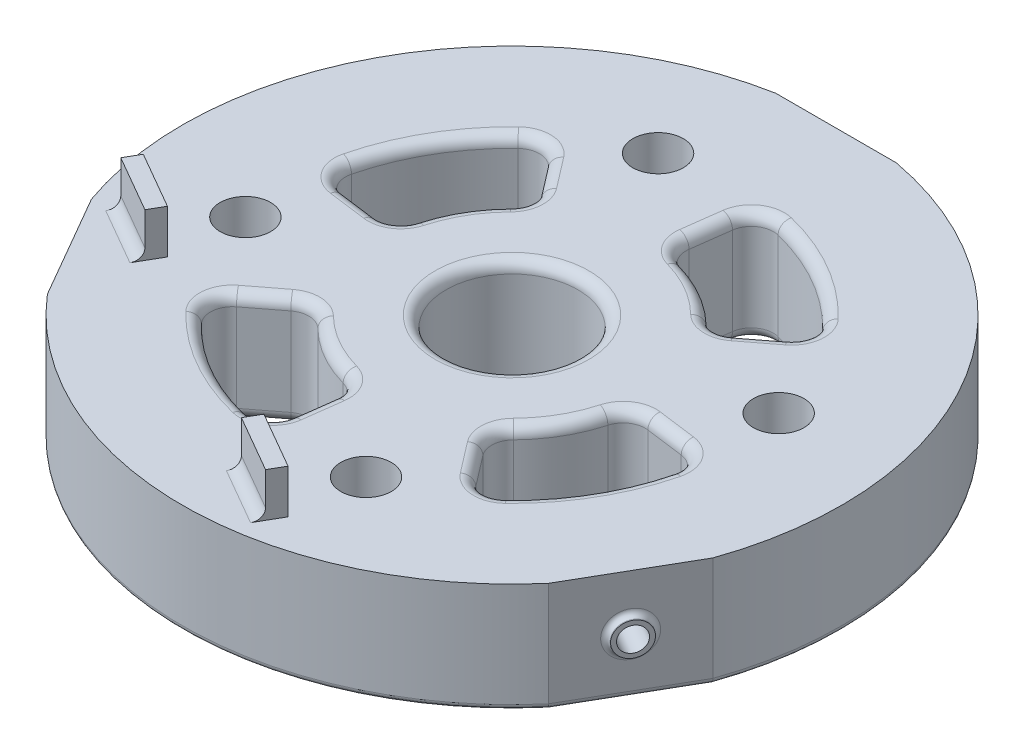
SolidWorks part; units mm, degrees
ref_plane "前视基准面" through (0, 0, 0) normal (0, 0, 1) x (1, 0, 0)
ref_plane "上视基准面" through (0, 0, 0) normal (0, 1, 0) x (1, 0, 0)
ref_plane "右视基准面" through (0, 0, 0) normal (1, 0, 0) x (0, 0, -1)
other "Configuration Table"
sketch "草图1" plane through (0, 0, 0) normal (0, 1, 0) x (1, 0, 0)
  line L0 (0, 0) -> (0, 30) construction
  line L1 (0, 0) -> (-25.9808, -15) construction
  line L2 (0, 0) -> (25.9808, -15) construction
  line L3 (-5.4819, 29.4949) -> (5.4819, 29.4949)
  line L4 (-5, 24.4949) -> (5, 24.4949)
  line L5 (28.2843, -10) -> (22.8024, -19.4949)
  line L6 (23.7132, -7.9173) -> (18.7132, -16.5776)
  line L7 (-22.8024, -19.4949) -> (-28.2843, -10)
  line L8 (-18.7132, -16.5776) -> (-23.7132, -7.9173)
  arc A0 (-5.4819, 29.4949) -> (-28.2843, -10) centre (0, 0) ccw
  arc A1 (-5, 24.4949) -> (-23.7132, -7.9173) centre (0, 0) ccw
  arc A2 (23.7132, -7.9173) -> (5, 24.4949) centre (0, 0) ccw
  arc A3 (28.2843, -10) -> (5.4819, 29.4949) centre (0, 0) ccw
  arc A4 (-18.7132, -16.5776) -> (18.7132, -16.5776) centre (0, 0) ccw
  arc A5 (-22.8024, -19.4949) -> (22.8024, -19.4949) centre (0, 0) ccw
  point P21 (0, 0)
  dimension "D1" = 60
  dimension "D2" = 50
  dimension "D3" = 120
  dimension "D4" = 120
  dimension "D5" = 5
  dimension "D6" = 10
  dimension "D7" = 3
extrude "凸台-拉伸1" add sketch "草图1" along normal blind 10
sketch "草图2" plane through (25.5433, 0, 14.7474) normal (0.866, 0, 0.5) x (0.5, 0, -0.866)
  circle A0 centre (0, 5) radius 1.1
  dimension "D1" = 2.2
  dimension "D2" = 5
extrude "切除-拉伸1" cut sketch "草图2" against normal blind 10
sketch "草图3" plane through (21.2132, 0, 12.2474) normal (-0.866, 0, -0.5) x (-0.5, 0, 0.866)
  line L0 (0, 10) -> (0, 0) construction
  circle A0 centre (0, 5) radius 3.1
  dimension "D1" = 6.2
  dimension "D2" = 5
extrude "切除-拉伸2" [suppressed] cut sketch "草图3" against normal blind 0.6
pattern_circular "阵列(圆周)1" count 3 over 360 about axis through (0, 10, 0) along (0, -1, 0) of "切除-拉伸1"
sketch "草图4" plane through (25.5433, 0, 14.7474) normal (0.866, 0, 0.5) x (0.5, 0, -0.866)
  circle A0 centre (0, 5) radius 1.1
  circle A1 centre (0, 5) radius 1.5
  dimension "D1" = 2.2
  dimension "D2" = 3
extrude "凸台-拉伸2" add sketch "草图4" along normal blind 0.6
fillet "圆角1" radius 0.5 1 edges at (24.7933, 5, 16.0465)
pattern_circular "阵列(圆周)2" count 3 over 360 about axis through (0, 0, 0) along (0, 1, 0) of "凸台-拉伸2"
fillet "圆角2" radius 0.5 2 edges at (1.5, 5, -29.4949) (-26.2933, 5, 13.4484)
sketch "草图5" plane through (0, 10, 0) normal (0, 1, 0) x (1, 0, 0)
  circle A0 centre (0, 0) radius 25
extrude "凸台-拉伸3" add sketch "草图5" against normal blind 10
sketch "草图6" plane through (0, 10, 0) normal (0, 1, 0) x (1, 0, 0)
  line L0 (10.1645, 17.6055) -> (0, 0) construction
  line L5 (0, 0) -> (16.3306, -9.4285) construction
  line L6 (-6.1154, 19.4078) -> (19.8654, 4.4078) construction
  line L7 (19.8654, 4.4078) -> (6.1154, -19.4078) construction
  line L8 (-6.1154, 19.4078) -> (-19.8654, -4.4078) construction
  line L9 (-19.8654, -4.4078) -> (6.1154, -19.4078) construction
  line L10 (0, 0) -> (25.5433, -14.7474) construction
  line L11 (24.5433, -16.4795) -> (26.5433, -13.0154) construction
  circle A0 centre (-6.1154, 19.4078) radius 2.3
  circle A1 centre (19.8654, 4.4078) radius 2.3
  circle A2 centre (6.1154, -19.4078) radius 2.3
  circle A3 centre (-19.8654, -4.4078) radius 2.3
  point P10 (-6.875, -11.9078)
  point P12 (6.875, 11.9078)
  point P13 (-12.9904, 7.5)
  point P14 (12.9904, -7.5)
  dimension "D3" = 4.6
  dimension "D1" = 30
  dimension "D2" = 27.5
extrude "切除-拉伸3" cut sketch "草图6" against normal blind 10
sketch "草图7" plane through (0, 0, 0) normal (0, -1, 0) x (1, 0, 0)
  circle A0 centre (-19.8654, 4.4078) radius 3.65
  circle A1 centre (6.1154, 19.4078) radius 3.65
  circle A2 centre (19.8654, -4.4078) radius 3.65
  circle A3 centre (-6.1154, -19.4078) radius 3.65
  dimension "D1" = 7.3
  dimension "D2" = 7.3
  dimension "D3" = 7.3
  dimension "D4" = 7.3
extrude "切除-拉伸4" cut sketch "草图7" against normal blind 4
sketch "草图8" plane through (0, 10, 0) normal (0, 1, 0) x (1, 0, 0)
  line L0 (-19.8654, -4.4078) -> (6.1154, -19.4078) construction
  line L1 (-22.8654, -9.604) -> (3.1154, -24.604) construction
  line L2 (-19.8654, -4.4078) -> (-22.8654, -9.604) construction
  line L3 (-20.2673, -11.104) -> (-25.4635, -8.104)
  line L4 (-25.4635, -8.104) -> (-26.2135, -9.403)
  line L5 (-26.2135, -9.403) -> (-21.0173, -12.403)
  line L6 (-20.2673, -11.104) -> (-21.0173, -12.403)
  line L7 (0, 0) -> (-6.875, -11.9078) construction
  line L8 (-25.4635, -8.104) -> (-26.2135, -9.403)
  line L9 (-20.2673, -11.104) -> (-21.0173, -12.403)
  line L10 (-25.4635, -8.104) -> (-26.2135, -9.403)
  line L11 (-20.2673, -11.104) -> (-21.0173, -12.403)
  line L12 (-25.4635, -8.104) -> (-26.2135, -9.403)
  line L13 (-20.2673, -11.104) -> (-21.0173, -12.403)
  line L14 (6.1154, -19.4078) -> (3.1154, -24.604) construction
  line L15 (0.5173, -23.104) -> (-0.2327, -24.403)
  line L16 (5.7135, -26.104) -> (4.9635, -27.403)
  line L17 (0.5173, -23.104) -> (-0.2327, -24.403)
  line L18 (5.7135, -26.104) -> (4.9635, -27.403)
  line L19 (0.5173, -23.104) -> (-0.2327, -24.403)
  line L20 (5.7135, -26.104) -> (4.9635, -27.403)
  line L21 (0.5173, -23.104) -> (-0.2327, -24.403)
  line L22 (4.9635, -27.403) -> (-0.2327, -24.403)
  line L23 (5.7135, -26.104) -> (4.9635, -27.403)
  line L24 (0.5173, -23.104) -> (5.7135, -26.104)
  point P13 (-23.6154, -10.903)
  point P23 (2.3654, -25.903)
  dimension "D2" = 1.5
  dimension "D3" = 6
  dimension "D1" = 6
extrude "凸台-拉伸4" add sketch "草图8" along normal blind 4 contours L6 L3 L4 L5 | L24 L15 L22 L16
fillet "圆角3" radius 1 2 edges at (2.3654, 10, 25.903) (-23.6154, 10, 10.903)
fillet "圆角4" radius 0.5 10 edges at (-25.5433, 0, 14.7474) (0, 0, 30) (25.5433, 0, 14.7474) (25.9808, 0, -15) (0, 0, -29.4949) (-25.9808, 0, -15) (-6.1154, 0, -23.0578) (19.8654, 0, -8.0578) (6.1154, 0, 15.7578) (-19.8654, 0, 0.7578)
sketch "草图9" plane through (0, 0, 0) normal (0, -1, 0) x (1, 0, 0)
  line L0 (6.1154, 19.4078) -> (19.8654, -4.4078) construction
  line L1 (0, 0) -> (12.9904, 7.5) construction
  line L4 (0, 0) -> (-10, 17.3205) construction
  line L11 (12.3931, 1.6316) -> (19.8289, 2.6105)
  line L12 (7.6095, 9.9169) -> (12.1752, 15.8671)
  line L13 (-1.6316, 12.3931) -> (-2.6105, 19.8289)
  line L14 (-9.9169, 7.6095) -> (-15.8671, 12.1752)
  line L15 (-12.3931, -1.6316) -> (-19.8289, -2.6105)
  line L16 (-7.6095, -9.9169) -> (-12.1752, -15.8671)
  line L17 (9.9169, -7.6095) -> (15.8671, -12.1752)
  line L18 (1.6316, -12.3931) -> (2.6105, -19.8289)
  circle A0 centre (0, 0) radius 6
  arc A1 (19.8289, 2.6105) -> (12.1752, 15.8671) centre (0, 0) ccw
  arc A2 (1.6316, -12.3931) -> (9.9169, -7.6095) centre (0, 0) ccw
  arc A3 (-2.6105, 19.8289) -> (-15.8671, 12.1752) centre (0, 0) ccw
  arc A4 (2.6105, -19.8289) -> (15.8671, -12.1752) centre (0, 0) ccw
  arc A5 (-19.8289, -2.6105) -> (-12.1752, -15.8671) centre (0, 0) ccw
  arc A6 (12.3931, 1.6316) -> (7.6095, 9.9169) centre (0, 0) ccw
  arc A7 (-12.3931, -1.6316) -> (-7.6095, -9.9169) centre (0, 0) ccw
  arc A8 (-1.6316, 12.3931) -> (-9.9169, 7.6095) centre (0, 0) ccw
  dimension "D1" = 12
  dimension "D2" = 40
  dimension "D3" = 25
extrude "切除-拉伸5" cut sketch "草图9" against normal blind 34
fillet "圆角5" radius 2 16 edges at (9.9169, 5, -7.6095) (1.6316, 5, -12.3931) (2.6105, 5, -19.8289) (15.8671, 5, -12.1752) (-7.6095, 5, -9.9169) (-12.3931, 5, -1.6316) (-12.1752, 5, -15.8671) (-19.8289, 5, -2.6105) (-15.8671, 5, 12.1752) (-9.9169, 5, 7.6095) (-2.6105, 5, 19.8289) (-1.6316, 5, 12.3931) (7.6095, 5, 9.9169) (12.3931, 5, 1.6316) (19.8289, 5, 2.6105) (12.1752, 5, 15.8671)
fillet "圆角6" radius 1 66 edges at (-9.8163, 10, -12.7928) (-12.3262, 10, -14.9688) (-17.3205, 10, -10) (-19.1264, 10, -3.1905) (-15.987, 10, -2.1047) (-12.8726, 10, -2.1904) (-10.8253, 10, -6.25) (-6.25, 10, 10.8253) (-10.0528, 10, 8.3332) (-12.7928, 10, 9.8163) (-14.9688, 10, 12.3262) (-10, 10, 17.3205) (-3.1905, 10, 19.1264) (-2.1047, 10, 15.987) (10, 10, -17.3205) (3.1905, 10, -19.1264) (2.1047, 10, -15.987) (2.1904, 10, -12.8726) (6.25, 10, -10.8253) (10.0528, 10, -8.3332) (12.7928, 10, -9.8163) (19.1264, 10, 3.1905) (17.3205, 10, 10) (12.3262, 10, 14.9688) (9.8163, 10, 12.7928) (8.3332, 10, 10.0528) (10.8253, 10, 6.25) (12.8726, 10, 2.1904) (-10.8253, 0, -6.25) (-12.8726, 0, -2.1904) (-15.987, 0, -2.1047) (-19.1264, 0, -3.1905) (-17.3205, 0, -10) (-12.3262, 0, -14.9688) (-9.8163, 0, -12.7928) (-6.25, 0, 10.8253) (-2.1904, 0, 12.8726) (-2.1047, 0, 15.987) (-3.1905, 0, 19.1264) (-10, 0, 17.3205) (-14.9688, 0, 12.3262) (-12.7928, 0, 9.8163) (12.8726, 0, 2.1904) (10.8253, 0, 6.25) (8.3332, 0, 10.0528) (9.8163, 0, 12.7928) (12.3262, 0, 14.9688) (17.3205, 0, 10) (19.1264, 0, 3.1905) (6.25, 0, -10.8253) (2.1904, 0, -12.8726) (2.1047, 0, -15.987) (3.1905, 0, -19.1264) (10, 0, -17.3205) (14.9688, 0, -12.3262) (12.7928, 0, -9.8163) (-8.3332, 10, -10.0528) (-2.1904, 10, 12.8726) (14.9688, 10, -12.3262) (0, 10, 6) (15.987, 10, 2.1047) (-8.3332, 0, -10.0528) (-10.0528, 0, 8.3332) (15.987, 0, 2.1047) (10.0528, 0, -8.3332) (0, 0, -6)
